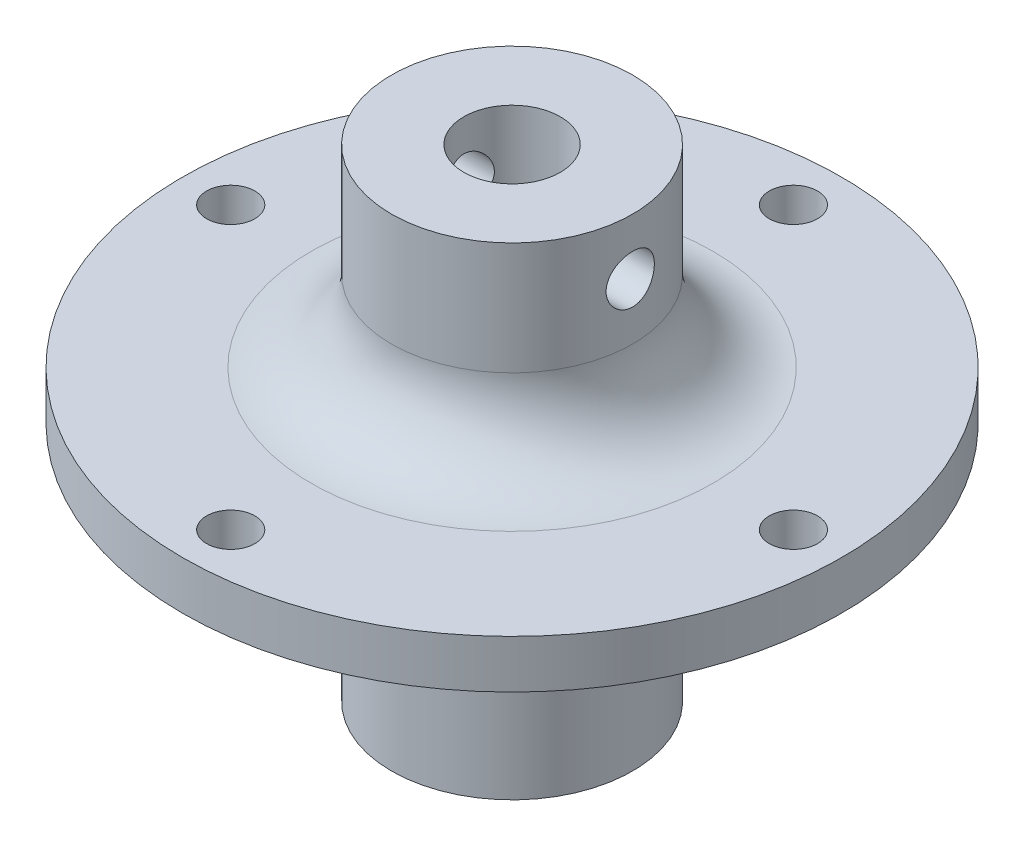
SolidWorks part; units mm, degrees
ref_plane "Front Plane" through (0, 0, 0) normal (0, 0, 1) x (1, 0, 0)
ref_plane "Top Plane" through (0, 0, 0) normal (0, 1, 0) x (1, 0, 0)
ref_plane "Right Plane" through (0, 0, 0) normal (1, 0, 0) x (0, 0, -1)
sketch "Sketch2" plane through (0, 0, 0) normal (0, 0, 1) x (1, 0, 0)
  line L0 (0, 9.7677) -> (0, -13.7898) construction
  line L1 (7.5, 30) -> (7.5, 18)
  line L2 (3, 30) -> (7.5, 30)
  line L3 (7.5, 18) -> (20.5, 18)
  line L4 (20.5, 18) -> (20.5, 15)
  line L6 (3, 0) -> (3, 30)
  line L7 (20.5, 15) -> (7.5, 15)
  line L8 (7.5, 15) -> (7.5, 0)
  line L9 (7.5, 0) -> (3, 0)
  dimension "D1" = 20.5
  dimension "D2" = 7.5
  dimension "D3" = 7.5
  dimension "D4" = 15
  dimension "D5" = 3
  dimension "D6" = 30
  dimension "D7" = 3
revolve "Revolve1" add sketch "Sketch2" angle 360 about L0
fillet "Fillet1" radius 5 1 edges at (0, 18, 7.5)
sketch "Sketch3" plane through (0, 18, 0) normal (0, 1, 0) x (1, 0, 0)
  circle A0 centre (0, 17.5) radius 1.5
  circle A2 centre (17.5, 0) radius 1.5
  circle A3 centre (0, -17.5) radius 1.5
  circle A4 centre (-17.5, 0) radius 1.5
  point P12 (0, 0)
  dimension "D2" = 3
  dimension "D1" = 17.5
  dimension "D3" = 4
extrude "Cut-Extrude2" cut sketch "Sketch3" against normal through all contours A0 | A2 | A3 | A4
ref_plane "Plane1" through (-7.5, 0, 0) normal (-1, 0, 0) x (0, 0, 1)
sketch "Sketch4" plane through (-7.5, 0, 0) normal (-1, 0, 0) x (0, 0, 1)
  line L0 (-7.5, 30) -> (7.5, 23)
  circle A0 centre (0, 26.5) radius 1.5
  dimension "D1" = 3
extrude "Cut-Extrude3" cut sketch "Sketch4" against normal through all both and the other way through all contours L0 A0 | L0 A0
